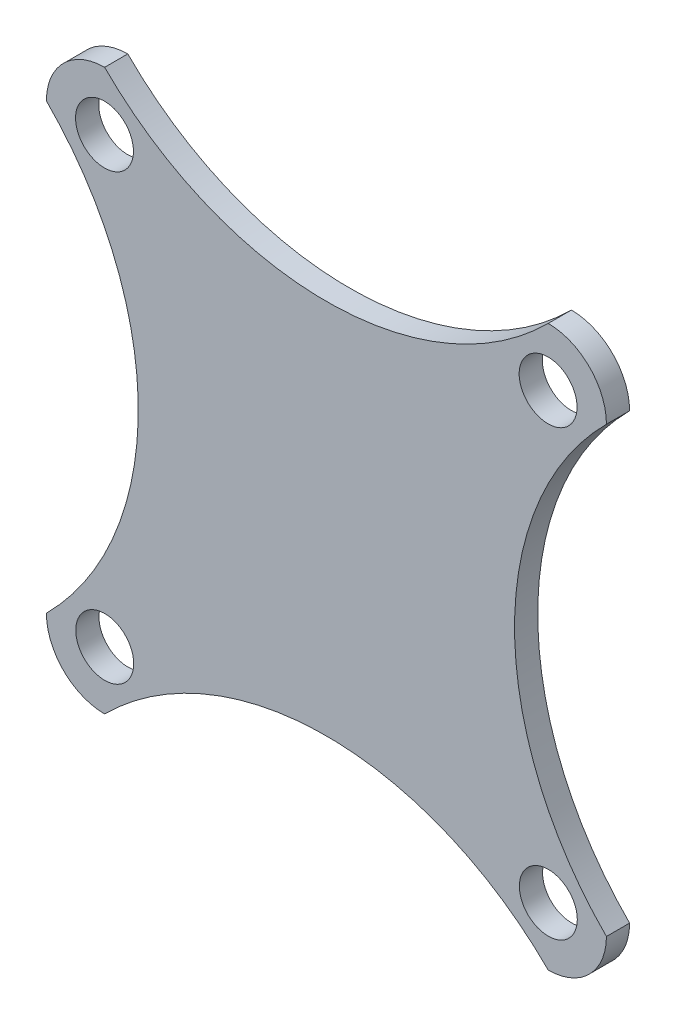
SolidWorks part; units mm, degrees
ref_plane "Front Plane" through (0, 0, 0) normal (0, 0, 1) x (1, 0, 0)
ref_plane "Top Plane" through (0, 0, 0) normal (0, 1, 0) x (1, 0, 0)
ref_plane "Right Plane" through (0, 0, 0) normal (1, 0, 0) x (0, 0, -1)
sketch "Model" plane through (0, 0, 0) normal (0, 0, 1) x (1, 0, 0)
  arc A0 (-46.7849, -61.7585) -> (-42.2615, -57.2351) centre (-46.7849, -57.2351) ccw
  arc A1 (-81.2551, -18.2415) -> (-46.7849, -18.2415) centre (-64.02, -1.0064) ccw
  arc A2 (-85.7785, -57.2351) -> (-85.7785, -22.7649) centre (-103.0136, -40) ccw
  arc A3 (-46.7849, -61.7585) -> (-81.2551, -61.7585) centre (-64.02, -78.9936) ccw
  arc A4 (-85.7785, -57.2351) -> (-81.2551, -61.7585) centre (-81.2551, -57.2351) ccw
  arc A5 (-42.2615, -22.7649) -> (-46.7849, -18.2415) centre (-46.7849, -22.7649) ccw
  arc A6 (-42.2615, -22.7649) -> (-42.2615, -57.2351) centre (-25.0264, -40) ccw
  arc A7 (-81.2551, -18.2415) -> (-85.7785, -22.7649) centre (-81.2551, -22.7649) ccw
  circle A8 centre (-46.7939, -22.7558) radius 1.75
  circle A9 centre (-46.7939, -22.7558) radius 2.25
  circle A10 centre (-46.7758, -57.2261) radius 2.25
  circle A11 centre (-46.7758, -57.2261) radius 1.75
  circle A12 centre (-81.2461, -57.2442) radius 2.25
  circle A13 centre (-81.2461, -57.2442) radius 1.75
  circle A14 centre (-81.2642, -22.7739) radius 2.25
  circle A15 centre (-81.2642, -22.7739) radius 1.75
  point P50 (0, 0)
extrude "Boss-Extrude1" add sketch "Model" along normal blind 1.8 contours A1 A7 A2 A4 A3 A0 A6 A5 A14 A12 A10 A9
